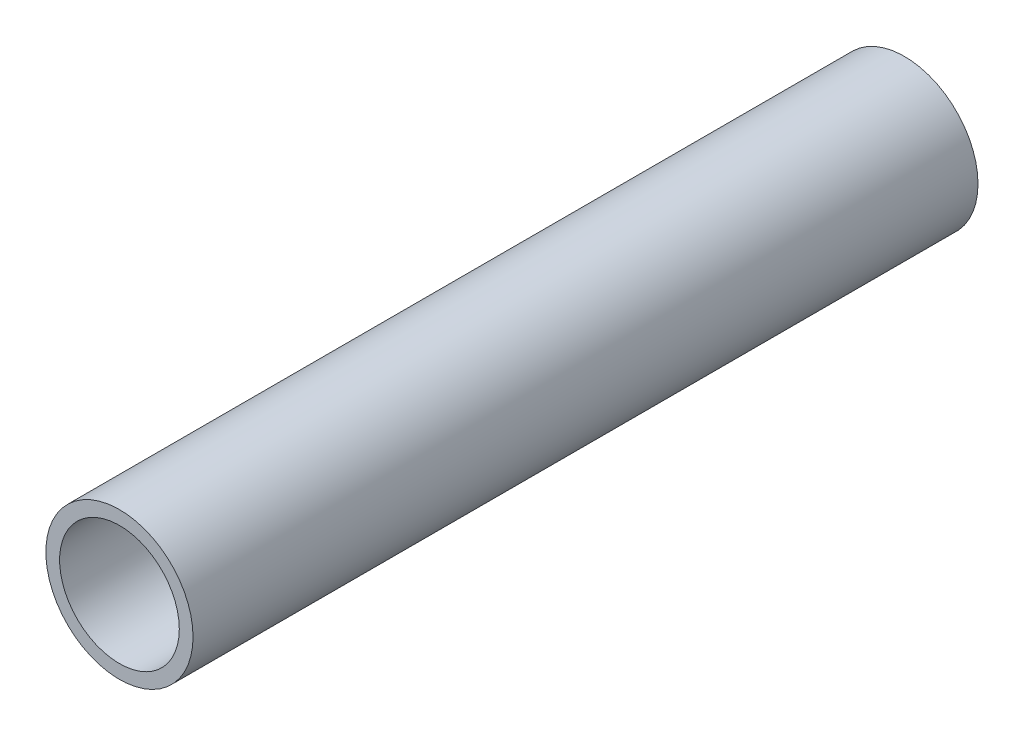
SolidWorks part; units mm, degrees
ref_plane "정면" through (0, 0, 0) normal (0, 0, 1) x (1, 0, 0)
ref_plane "윗면" through (0, 0, 0) normal (0, 1, 0) x (1, 0, 0)
ref_plane "우측면" through (0, 0, 0) normal (1, 0, 0) x (0, 0, -1)
sketch "스케치1" plane through (0, 0, 0) normal (0, 1, 0) x (1, 0, 0)
  line L0 (7.5, 0) -> (6.1, 0)
  line L1 (6.1, 0) -> (6.1, -200)
  line L2 (6.1, -200) -> (7.5, -200)
  line L3 (7.5, -200) -> (7.5, 0)
  line L4 (0, 0) -> (0, -200) construction
revolve "회전1" add sketch "스케치1" angle 360 about L4
sketch "스케치2" plane through (0, 0, 200) normal (0, 0, 1) x (1, 0, 0)
  circle A1 centre (0, 0) radius 7.5
  circle A2 centre (0, 0) radius 7.5
  dimension "D1" = 0
extrude "컷-돌출1" cut sketch "스케치2" against normal blind 120
